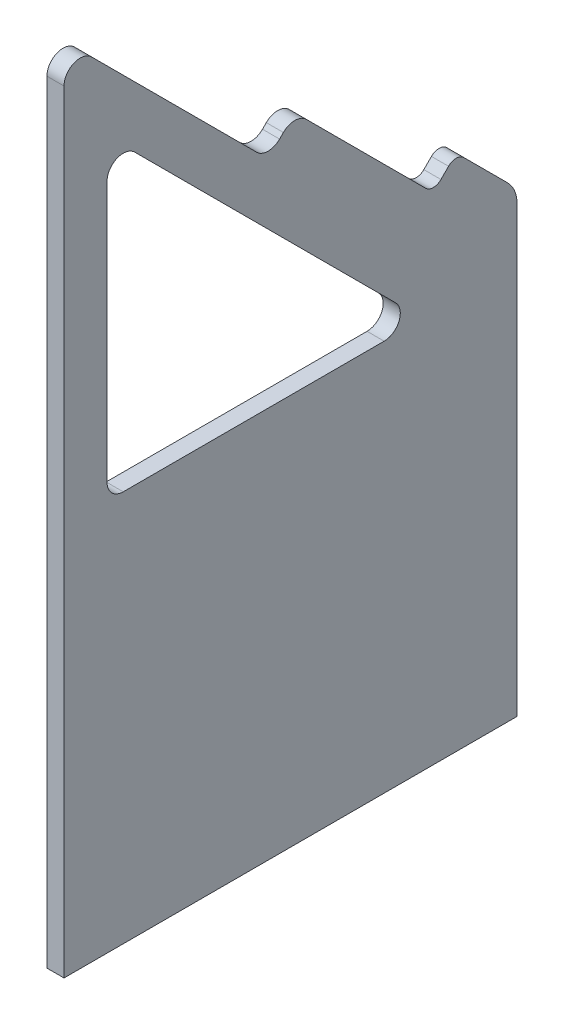
SolidWorks part; units mm, degrees
ref_plane "Plan de face" through (0, 0, 0) normal (0, 0, 1) x (1, 0, 0)
ref_plane "Plan de dessus" through (0, 0, 0) normal (0, 1, 0) x (1, 0, 0)
ref_plane "Plan de droite" through (0, 0, 0) normal (1, 0, 0) x (0, 0, -1)
sketch "Esquisse1" plane through (0, 0, 0) normal (1, 0, 0) x (0, 0, -1)
  line L0 (-42.0729, 0) -> (42.0729, 0)
  line L1 (42.0729, 0) -> (42.0729, 84.9497)
  line L2 (42.0729, 84.9497) -> (30.7591, 96.2635)
  line L3 (30.7591, 96.2635) -> (26.5165, 92.0208)
  line L4 (26.5165, 92.0208) -> (33.5876, 84.9497)
  line L5 (33.5876, 84.9497) -> (28.6378, 80)
  line L6 (28.6378, 80) -> (-42.0729, 150.7107)
  line L7 (-42.0729, 150.7107) -> (-42.0729, 0)
  point P9 (30.052, 88.4853)
  point P12 (0, 0)
  dimension "D1" = 45
  dimension "D2" = 7
  dimension "D3" = 6
  dimension "D4" = 80
  dimension "D5" = 100
  dimension "D6" = 10
extrude "Boss.-Extru.1" add sketch "Esquisse1" along normal blind 3.175
sketch "Esquisse2" plane through (3.175, 0, 0) normal (1, 0, 0) x (0, 0, -1)
  line L0 (-42.0729, 0) -> (42.0729, 0) construction
  line L1 (-10, 0) -> (10, 0)
  line L2 (-10, 0) -> (-10, 6.35)
  line L3 (-10, 6.35) -> (10, 6.35)
  line L4 (10, 0) -> (10, 6.35)
  line L15 (-10, 52.7) -> (10, 52.7)
  line L16 (-10, 52.7) -> (-10, 46.35)
  line L17 (-10, 46.35) -> (10, 46.35)
  line L18 (10, 52.7) -> (10, 46.35)
  line L19 (42.0729, 0) -> (42.0729, 84.9497) construction
  line L29 (42.0729, 36.35) -> (35.7229, 36.35)
  line L30 (42.0729, 36.35) -> (42.0729, 16.35)
  line L31 (42.0729, 16.35) -> (35.7229, 16.35)
  line L32 (35.7229, 36.35) -> (35.7229, 16.35)
  point P6 (0, 0)
  point P22 (35.7229, 26.35)
  dimension "D1" = 20
  dimension "D3" = 6.35
  dimension "D5" = 40
  dimension "D6" = 26.35
fillet "Congé1" radius 6 1 edges at (1.5875, 84.9497, -42.0729)
fillet "Congé2" radius 2 2 edges at (1.5875, 92.0208, -26.5165) (1.5875, 96.2635, -30.7591)
sketch "Esquisse4" plane through (3.175, 0, 0) normal (1, 0, 0) x (0, 0, -1)
  line L0 (24.6241, 72.7) -> (-34.0729, 72.7)
  line L1 (-34.0729, 72.7) -> (-34.0729, 131.397)
  line L2 (-34.0729, 131.397) -> (24.6241, 72.7)
  line L3 (28.6378, 80) -> (-42.0729, 150.7107) construction
  line L4 (-42.0729, 150.7107) -> (-42.0729, 0) construction
  line L6 (-10, 52.7) -> (10, 52.7) construction
  dimension "D1" = 8
  dimension "D2" = 8
  dimension "D3" = 20
extrude "Enlèv. mat.-Extru.2" cut sketch "Esquisse4" against normal through all
fillet "Congé4" radius 3 4 edges at (1.5875, 72.7, -24.6241) (1.5875, 72.7, 34.0729) (1.5875, 131.397, 34.0729) (1.5875, 150.7107, 42.0729)
sketch "Esquisse5" plane through (3.175, 0, 0) normal (1, 0, 0) x (0, 0, -1)
  line L0 (27.9307, 90.6066) -> (33.5876, 84.9497) construction
  line L1 (30.7591, 96.2635) -> (26.5165, 92.0208)
  line L2 (26.5165, 92.0208) -> (0.7929, 117.7444)
  line L3 (0.7929, 117.7444) -> (-4.1569, 112.7947)
  line L4 (28.6378, 80) -> (-36.9515, 145.5894) construction
  line L5 (40.3155, 86.7071) -> (32.1734, 94.8492) construction
  line L6 (-4.1569, 112.7947) -> (28.6378, 80)
  line L7 (28.6378, 80) -> (37.8302, 89.1924)
  line L8 (37.8302, 89.1924) -> (30.7591, 96.2635)
  line L9 (29.3449, 94.8492) -> (27.9307, 93.435) construction
  point P0 (23.9264, 98.242)
  point P3 (-4.1569, 112.7947)
extrude "Boss.-Extru.2" add sketch "Esquisse5" against normal up to surface (3.175 mm away) up to face at (0, 91.622, 15.1508)
fillet "Congé5" radius 2 2 edges at (1.5875, 92.0208, -26.5165) (1.5875, 96.2635, -30.7591)
fillet "Congé6" radius 3 2 edges at (1.5875, 112.7947, 4.1569) (1.5875, 117.7444, -0.7929)
